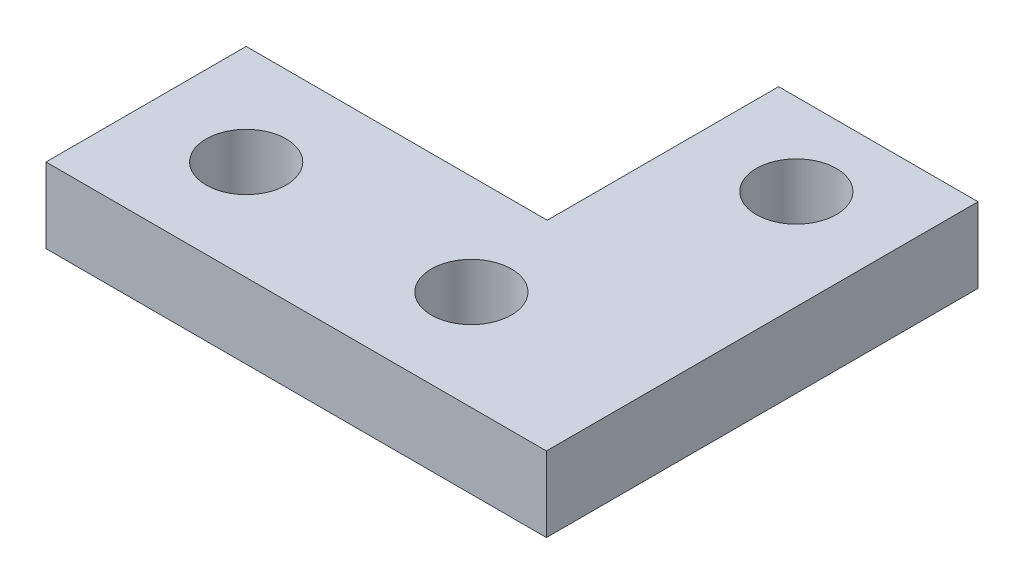
SolidWorks part; units mm, degrees
ref_plane "前视基准面" through (0, 0, 0) normal (0, 0, 1) x (1, 0, 0)
ref_plane "上视基准面" through (0, 0, 0) normal (0, 1, 0) x (1, 0, 0)
ref_plane "右视基准面" through (0, 0, 0) normal (1, 0, 0) x (0, 0, -1)
sketch "草图1" plane through (0, 0, 0) normal (0, 1, 0) x (1, 0, 0)
  line L0 (8.5, 8.3214) -> (8.5, -3.6479) construction
  line L1 (0, 0) -> (20, 0)
  line L2 (0, 0) -> (0, 8)
  line L3 (0, 8) -> (12.0322, 8)
  line L4 (20, 0) -> (20, 8)
  line L5 (0, 4) -> (25.8361, 4) construction
  line L6 (12.0322, 8) -> (12.0322, 17.2474)
  line L7 (12.0322, 17.2474) -> (20, 17.2474)
  line L8 (20, 17.2474) -> (20, 8)
  line L9 (16.0161, 17.2474) -> (16.0161, 8) construction
  circle A0 centre (4, 4) radius 1.6
  circle A1 centre (13, 4) radius 1.6
  circle A2 centre (16.0161, 13.9713) radius 1.6
  point P20 (16.0161, 13.9713)
  dimension "D1" = 3.2
  dimension "D4" = 9
  dimension "D5" = 4
  dimension "D2" = 20
  dimension "D3" = 8
extrude "凸台-拉伸1" add sketch "草图1" along normal blind 3
